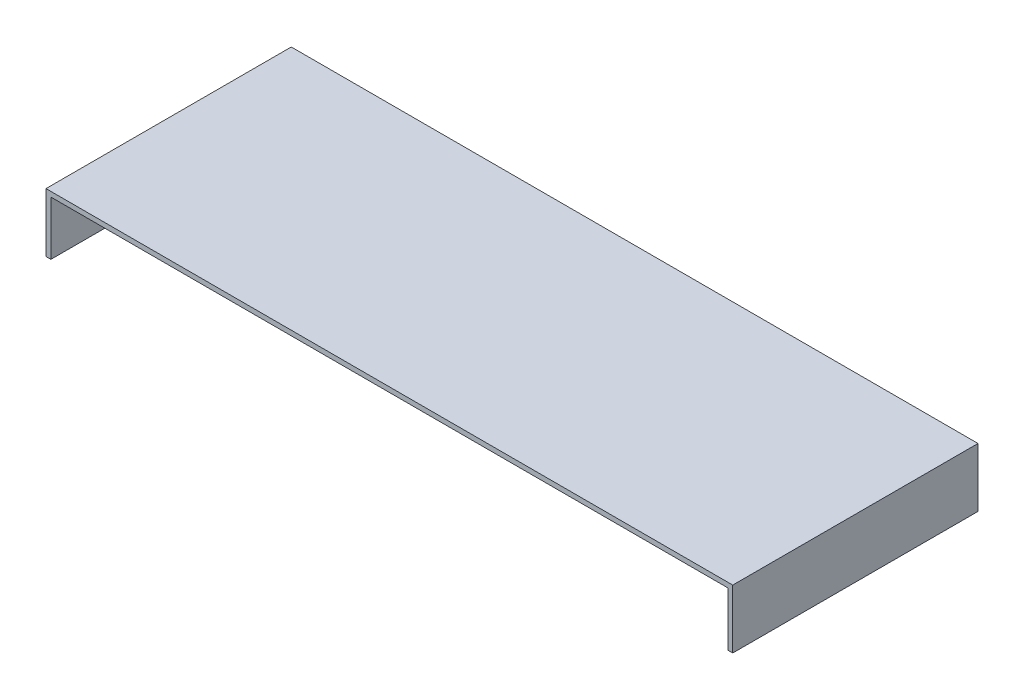
SolidWorks part; units mm, degrees
ref_plane "Front Plane" through (0, 0, 0) normal (0, 0, 1) x (1, 0, 0)
ref_plane "Top Plane" through (0, 0, 0) normal (0, 1, 0) x (1, 0, 0)
ref_plane "Right Plane" through (0, 0, 0) normal (1, 0, 0) x (0, 0, -1)
sketch "Sketch1" plane through (0, 0, 0) normal (0, 1, 0) x (1, 0, 0)
  line L1 (-350, -125) -> (350, -125)
  line L2 (-350, -125) -> (-350, 125)
  line L3 (-350, 125) -> (350, 125)
  line L4 (350, -125) -> (350, 125)
  line L5 (-350, -125) -> (350, 125) construction
  line L6 (-350, 125) -> (350, -125) construction
  point P0 (0, 0)
  dimension "D1" = 700
  dimension "D2" = 250
extrude "Boss-Extrude1" add sketch "Sketch1" along normal blind 60
shell "Shell1" thickness 5
sketch "Sketch3" plane through (0, 0, 125) normal (0, 0, 1) x (1, 0, 0)
  line L0 (-350, 0) -> (350, 0) construction
  line L1 (-345, 0) -> (345, 0)
  line L2 (-345, 0) -> (-345, 55)
  line L3 (-345, 55) -> (345, 55)
  line L4 (345, 0) -> (345, 55)
  line L5 (-350, 60) -> (-350, 0) construction
  line L6 (-350, 60) -> (350, 60) construction
  line L7 (350, 60) -> (350, 0) construction
  dimension "D1" = 5
  dimension "D2" = 5
  dimension "D3" = 5
extrude "Cut-Extrude1" cut sketch "Sketch3" against normal through all
